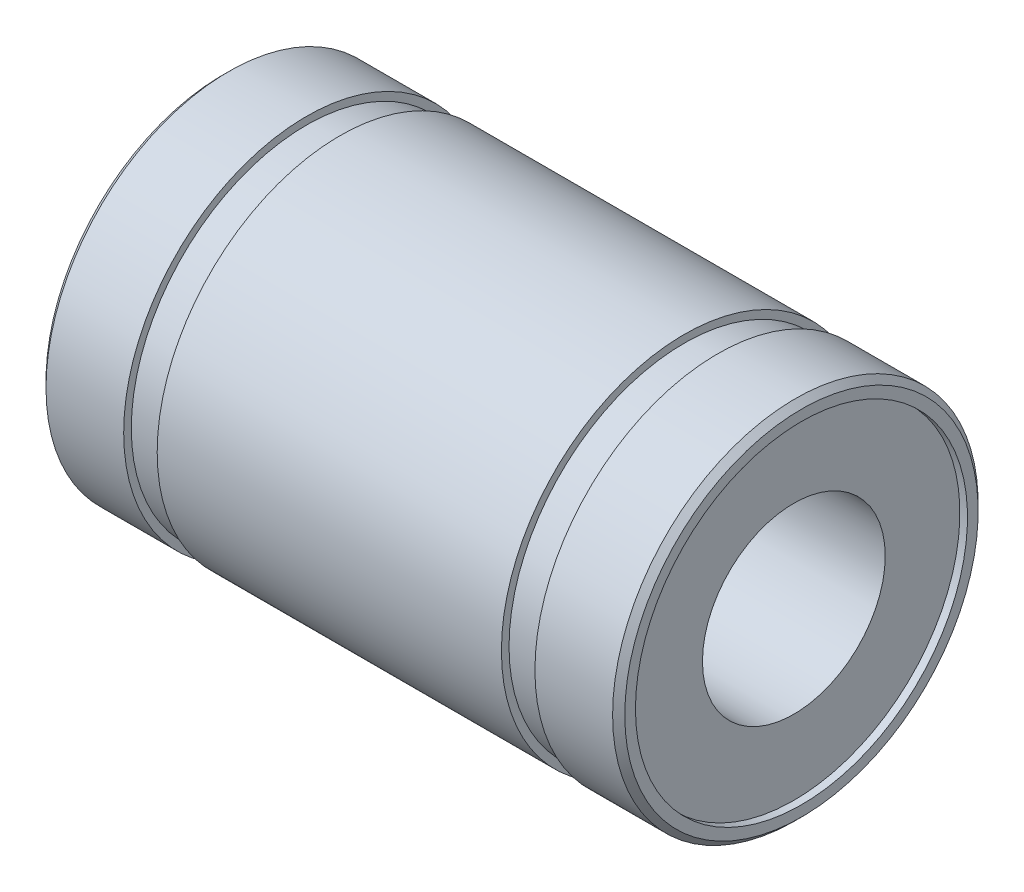
SolidWorks part; units mm, degrees
ref_plane "Front Plane" through (0, 0, 0) normal (0, 0, 1) x (1, 0, 0)
ref_plane "Top Plane" through (0, 0, 0) normal (0, 1, 0) x (1, 0, 0)
ref_plane "Right Plane" through (0, 0, 0) normal (1, 0, 0) x (0, 0, -1)
sketch "Sketch1" plane through (0, 0, 0) normal (0, 0, 1) x (1, 0, 0)
  line L0 (0, 0) -> (112.5581, 0) construction
  line L1 (0.25, 3) -> (0.25, 5.45)
  line L2 (0.25, 5.45) -> (0, 5.45)
  line L3 (0, 5.45) -> (0, 6)
  line L4 (0, 6) -> (2.75, 6)
  line L5 (2.75, 6) -> (2.75, 5.75)
  line L6 (2.75, 5.75) -> (3.85, 5.75)
  line L7 (3.85, 5.75) -> (3.85, 6)
  line L8 (3.85, 6) -> (15.15, 6)
  line L9 (15.15, 6) -> (15.15, 5.75)
  line L10 (15.15, 5.75) -> (16.25, 5.75)
  line L11 (16.25, 5.75) -> (16.25, 6)
  line L12 (16.25, 6) -> (19, 6)
  line L13 (19, 6) -> (19, 5.45)
  line L14 (19, 5.45) -> (18.75, 5.45)
  line L15 (18.75, 5.45) -> (18.75, 3)
  line L16 (18.75, 3) -> (0.25, 3)
  dimension "D1" = 6
  dimension "D2" = 12
  dimension "D3" = 1.1
  dimension "D4" = 13.5
  dimension "D5" = 19
  dimension "D6" = 11.5
  dimension "D7" = 0.3
revolve "Revolve1" add sketch "Sketch1" angle 360 about L0
chamfer "Chamfer1" distance 0.2 angle 45 2 edges at (19, 0, 6) (0, 0, 6)
